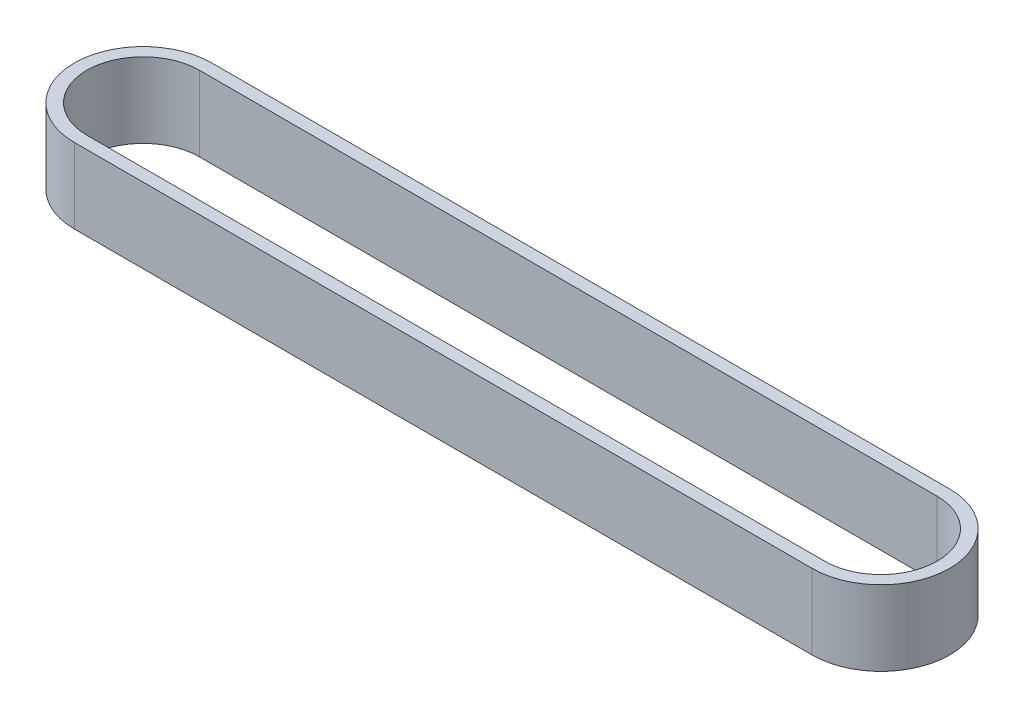
SolidWorks part; units mm, degrees
ref_plane "前视基准面" through (0, 0, 0) normal (0, 0, 1) x (1, 0, 0)
ref_plane "上视基准面" through (0, 0, 0) normal (0, 1, 0) x (1, 0, 0)
ref_plane "右视基准面" through (0, 0, 0) normal (1, 0, 0) x (0, 0, -1)
sketch "草图1" plane through (0, 0, 0) normal (0, 1, 0) x (1, 0, 0)
  line L0 (-29.5, 0) -> (29.5, 0) construction
  line L1 (-29.5, 4.5) -> (29.5, 4.5)
  line L2 (-29.5, -4.5) -> (29.5, -4.5)
  arc A0 (-29.5, 4.5) -> (-29.5, -4.5) centre (-29.5, 0) ccw
  arc A1 (29.5, -4.5) -> (29.5, 4.5) centre (29.5, 0) ccw
  point P2 (0, 0)
  dimension "D1" = 4.5
  dimension "D2" = 59
extrude "拉伸-薄壁1" add sketch "草图1" along normal blind 6 thin thin type one direction wall 1
